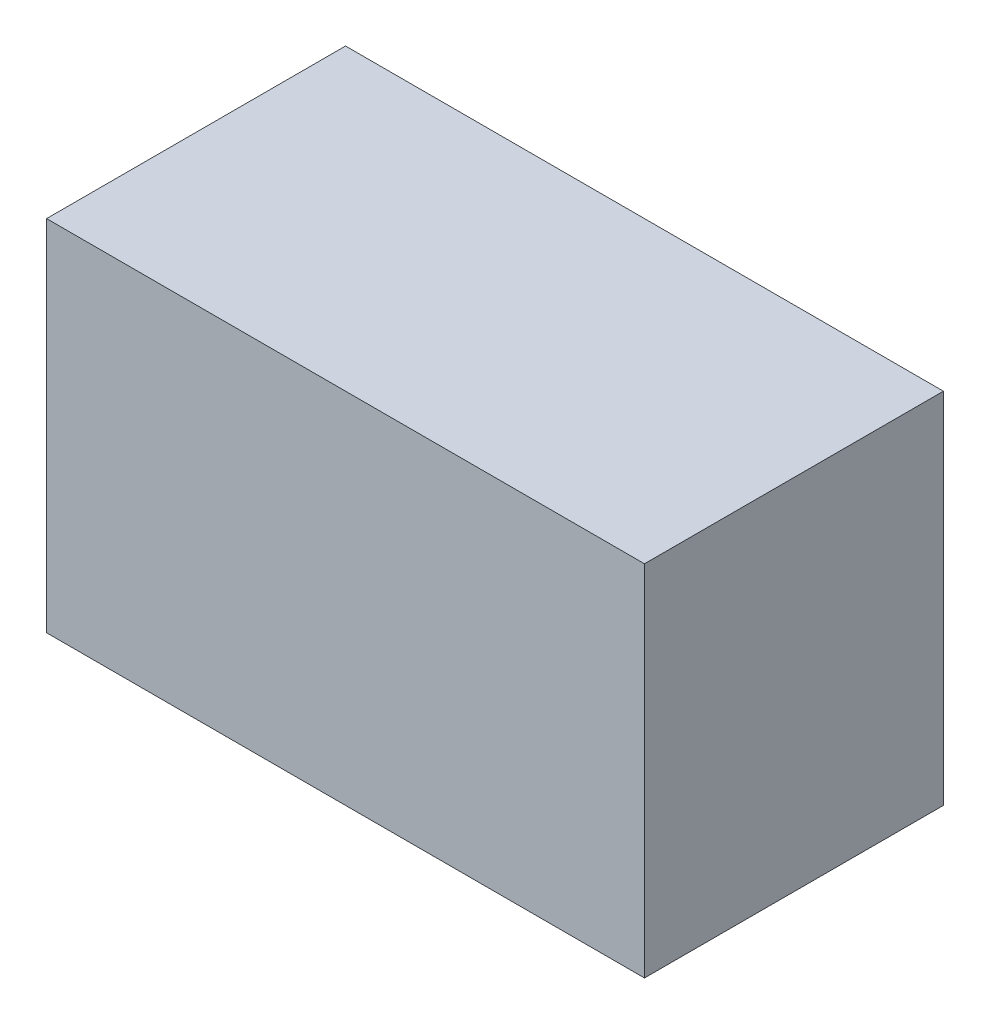
SolidWorks part; units mm, degrees
ref_plane "Plan de face" through (0, 0, 0) normal (0, 0, 1) x (1, 0, 0)
ref_plane "Plan de dessus" through (0, 0, 0) normal (0, 1, 0) x (1, 0, 0)
ref_plane "Plan de droite" through (0, 0, 0) normal (1, 0, 0) x (0, 0, -1)
sketch "Esquisse1" plane through (0, 0, 0) normal (0, 0, 1) x (1, 0, 0)
  line L1 (0, 0) -> (100, 0)
  line L2 (0, 0) -> (0, 60)
  line L3 (0, 60) -> (100, 60)
  line L4 (100, 0) -> (100, 60)
  dimension "D1" = 100
  dimension "D2" = 60
extrude "Boss.-Extru.1" add sketch "Esquisse1" along normal blind 50
